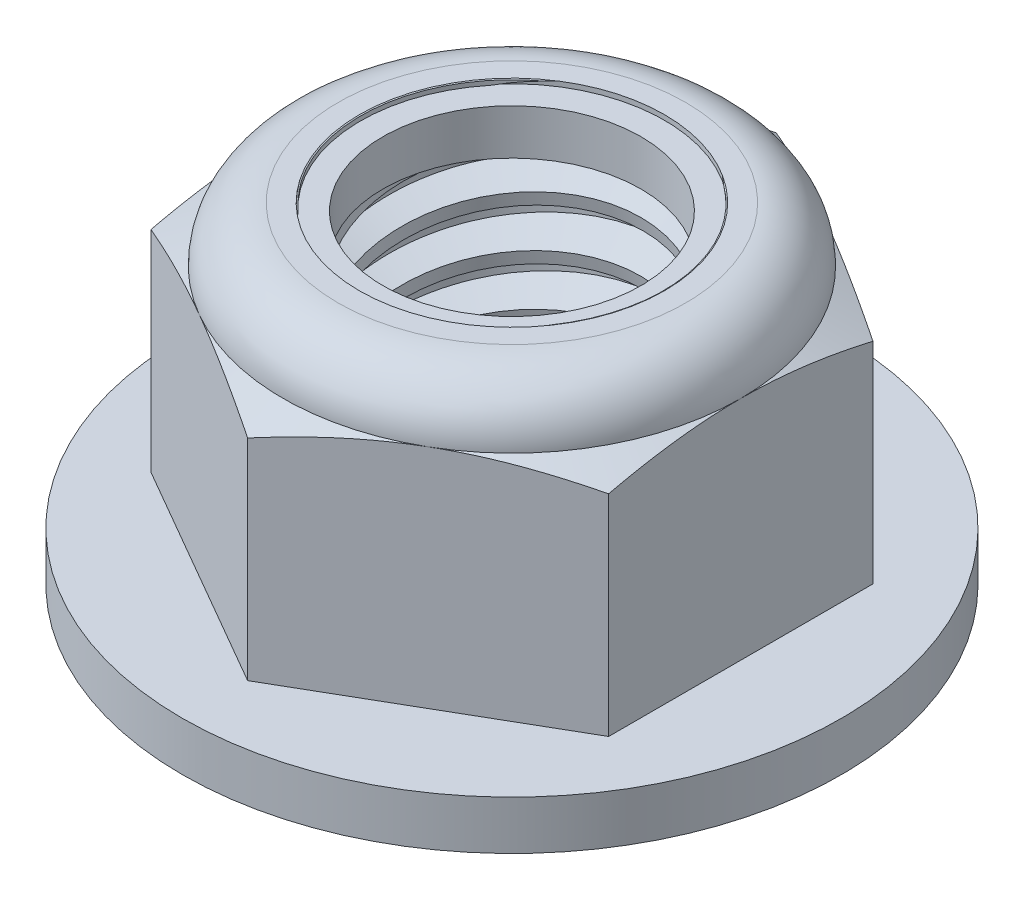
SolidWorks part; units mm, degrees
ref_plane "Front" through (0, 0, 0) normal (0, 0, 1) x (1, 0, 0)
ref_plane "Top" through (0, 0, 0) normal (0, 1, 0) x (1, 0, 0)
ref_plane "Right" through (0, 0, 0) normal (1, 0, 0) x (0, 0, -1)
sketch "Sketch1" plane through (0, 0, 0) normal (0, 1, 0) x (1, 0, 0)
  line L1 (0, 8.2489) -> (-7.1438, 4.1244)
  line L2 (-7.1438, 4.1244) -> (-7.1438, -4.1244)
  line L3 (-7.1438, -4.1244) -> (0, -8.2489)
  line L4 (0, -8.2489) -> (7.1437, -4.1244)
  line L5 (7.1437, -4.1244) -> (7.1437, 4.1244)
  line L6 (7.1437, 4.1244) -> (0, 8.2489)
  circle A0 centre (0, 0) radius 7.1438 construction
  dimension "Hex Flats" = 14.2875
extrude "Extrude1" add sketch "Sketch1" along normal blind 10.3187
sketch "Sketch8" plane through (0, 0, 0) normal (1, 0, 0) x (0, 0, -1)
  line L0 (0, 0) -> (10.287, 0)
  line L1 (10.287, 0) -> (10.287, 1.524)
  line L2 (10.287, 1.524) -> (0, 1.524)
  line L3 (0, 1.524) -> (0, 0)
  line L4 (0, 0) -> (0, -1.524) construction
  dimension "Flange Height" = 1.524
  dimension "Flange Dia" = 20.574
revolve "Revolve3" add sketch "Sketch8" angle 360 about L4
sketch "Sketch2" plane through (0, 0, 0) normal (1, 0, 0) x (0, 0, -1)
  line L0 (-4.7625, 0) -> (-4.7625, 10.3187) construction
  line L1 (0, 0) -> (4.7625, 0)
  line L2 (0, 0) -> (0, 10.3187)
  line L3 (0, 10.3187) -> (4.7625, 10.3187)
  line L4 (4.7625, 0) -> (4.7625, 10.3187)
  line L5 (-4.1244, 10.3187) -> (4.1244, 10.3187) construction
  line L7 (0, -4.7625) -> (0, 0) construction
  dimension "Thread Dia" = 9.525
revolve "Revolve1" add sketch "Sketch2" angle 360 about L7
sketch "Sketch3" plane through (0, 0, 0) normal (1, 0, 0) x (0, 0, -1)
  line L0 (4.7625, 10.3187) -> (-4.7625, 10.3187) construction
  line L1 (-4.7625, 10.3187) -> (-4.7625, 8.7312) construction
  line L2 (-4.7625, 8.7312) -> (4.7625, 10.3187) construction
  line L3 (4.7625, 10.3187) -> (4.7951, 10.123) construction
  line L4 (4.7951, 10.123) -> (5.0235, 8.7528)
  line L5 (5.0235, 8.7528) -> (4.0944, 9.1009)
  line L6 (4.0944, 9.1009) -> (4.0291, 9.4924)
  line L7 (4.0291, 9.4924) -> (4.7951, 10.123)
  line L8 (4.0617, 9.2967) -> (4.9093, 9.4379) construction
  line L9 (4.7625, 10.3187) -> (4.7625, 9.4135) construction
  line L10 (4.7625, 9.4135) -> (-4.7625, 7.826) construction
  line L11 (-4.7625, 7.826) -> (-4.7625, 8.7312) construction
  line L12 (-0.2832, 10.3187) -> (0.2832, 6.9207) construction
  line L13 (-4.7625, 0) -> (-4.7625, 10.3187) construction
  line L14 (0, 10.3187) -> (4.7625, 10.3187) construction
  line L15 (4.7625, 0) -> (4.7625, 10.3187) construction
  point P13 (0, 8.6197)
  dimension "D1" = 0.1984
  dimension "D2" = 0.3969
  dimension "Thread Pitch" = 1.5875
  dimension "D4" = 60
  dimension "D5" = 1.5875
revolve "Cut-Revolve1" cut sketch "Sketch3" angle 360 about L12
pattern_linear "LPattern1" count 7 spacing 1.5875 along (0, -1, 0) count 2 spacing 1.5875 along (0, 1, 0) of "Cut-Revolve1"
sketch "Sketch4" plane through (0, 0, 0) normal (1, 0, 0) x (0, 0, -1)
  line L0 (0, 10.3187) -> (4.7625, 10.3187)
  line L1 (4.7625, 10.3187) -> (4.0291, 9.9768)
  line L2 (4.0291, 9.9768) -> (4.0291, 0.342)
  line L3 (4.0291, 0.342) -> (4.7625, 0)
  line L4 (4.7625, 0) -> (0, 0)
  line L5 (0, 0) -> (0, 10.3187)
  line L6 (4.7625, 0) -> (4.7625, 10.3187) construction
  line L7 (0, 10.3187) -> (4.7625, 10.3187) construction
  line L8 (0, 0) -> (4.7625, 0) construction
  line L9 (0, 0) -> (0, 10.3187) construction
  line L10 (0, 10.3187) -> (0, 11.128) construction
  dimension "D1" = 25
revolve "Cut-Revolve2" cut sketch "Sketch4" angle 360 about L10
combine bodies "Combine1" operation type subtract main body 112 bodies to subtract 111
sketch "Sketch5" plane through (0, 0, 0) normal (1, 0, 0) x (0, 0, -1)
  line L0 (10.287, 1.524) -> (0, 1.524) construction
  line L1 (0, 0) -> (10.287, 0) construction
  line L2 (8.2489, 1.524) -> (8.2489, 8.0836)
  line L3 (8.2489, 8.0836) -> (7.1438, 8.599)
  line L4 (5.424, 10.3187) -> (5.424, 11.5887)
  line L5 (5.424, 11.5887) -> (9.5189, 11.5887)
  line L6 (9.5189, 11.5887) -> (9.5189, 1.524)
  line L9 (7.1438, 8.599) -> (7.1438, 0) construction
  line L13 (8.2489, 1.524) -> (9.5189, 1.524)
  line L15 (0, 0) -> (0, 11.5887) construction
  line L20 (0, 11.5887) -> (5.424, 11.5887) construction
  line L22 (0, 10.3187) -> (4.7625, 10.3187) construction
  arc A0 (7.1438, 8.599) -> (5.424, 10.3187) centre (5.424, 8.599) ccw
  dimension "D4" = 1.7198
  dimension "D1" = 1.27
  dimension "D2" = 115
  dimension "D3" = 10.3187
revolve "Cut-Revolve3" cut sketch "Sketch5" angle 360 about L15
sketch "Sketch6" plane through (0, 0, 0) normal (1, 0, 0) x (0, 0, -1)
  line L0 (0, 8.599) -> (6.9914, 8.599)
  line L1 (5.424, 10.1663) -> (4.7265, 10.1663)
  line L2 (0, 11.5887) -> (0, 8.599)
  line L3 (4.7265, 11.5887) -> (0, 11.5887)
  line L4 (0, 11.5887) -> (5.424, 11.5887) construction
  line L5 (0, 0) -> (0, 11.5887) construction
  line L6 (0, 11.5887) -> (0, 44.323) construction
  line L7 (4.7265, 10.1663) -> (4.7265, 11.5887)
  line L8 (5.424, 10.3187) -> (5.424, 10.1663) construction
  line L9 (4.7265, 10.1663) -> (4.0291, 10.1663) construction
  line L10 (4.0291, 10.1663) -> (4.0291, 9.9768) construction
  arc A0 (6.9914, 8.599) -> (5.424, 10.1663) centre (5.424, 8.599) ccw
  arc A1 (7.1438, 8.599) -> (5.424, 10.3187) centre (5.424, 8.599) ccw construction
  dimension "D1" = 0.1524
revolve "Cut-Revolve4" cut sketch "Sketch6" angle 360 about L6
sketch "Sketch7" plane through (0, 0, 0) normal (1, 0, 0) x (0, 0, -1)
  line L0 (4.0291, 8.6752) -> (6.9132, 8.6752)
  line L1 (5.424, 10.0901) -> (4.0291, 10.0901)
  line L2 (4.0291, 10.0901) -> (4.0291, 8.6752)
  line L3 (4.0291, 8.6752) -> (0, 8.6752) construction
  line L4 (0, 8.6752) -> (0, 10.0901) construction
  line L5 (0, 10.0901) -> (4.0291, 10.0901) construction
  line L6 (4.0291, 8.6752) -> (4.0291, 8.599) construction
  line L7 (0, 8.599) -> (6.9914, 8.599) construction
  line L8 (5.424, 10.0901) -> (5.424, 10.1663) construction
  arc A0 (6.9132, 8.6752) -> (5.424, 10.0901) centre (5.424, 8.599) ccw
  arc A2 (6.9914, 8.599) -> (5.424, 10.1663) centre (5.424, 8.599) ccw construction
  dimension "D1" = 0.0762
revolve "Revolve2" add sketch "Sketch7" angle 360 about L4
equation "\"D1@Sketch3\"=\"Thread Pitch@Sketch3\"/8"
equation "\"D2@Sketch3\"=\"Thread Pitch@Sketch3\"/4"
equation "\"D5@Sketch3\"=\"Thread Pitch@Sketch3\""
equation "\"D4@LPattern1\"=\"Thread Pitch@Sketch3\""
equation "\"D3@LPattern1\"=\"Thread Pitch@Sketch3\""
equation "\"D1@LPattern1\"=\"Height@Extrude1\"/\"Thread Pitch@Sketch3\""
equation "\"D4@Sketch5\"=\"Height@Extrude1\"/6"
